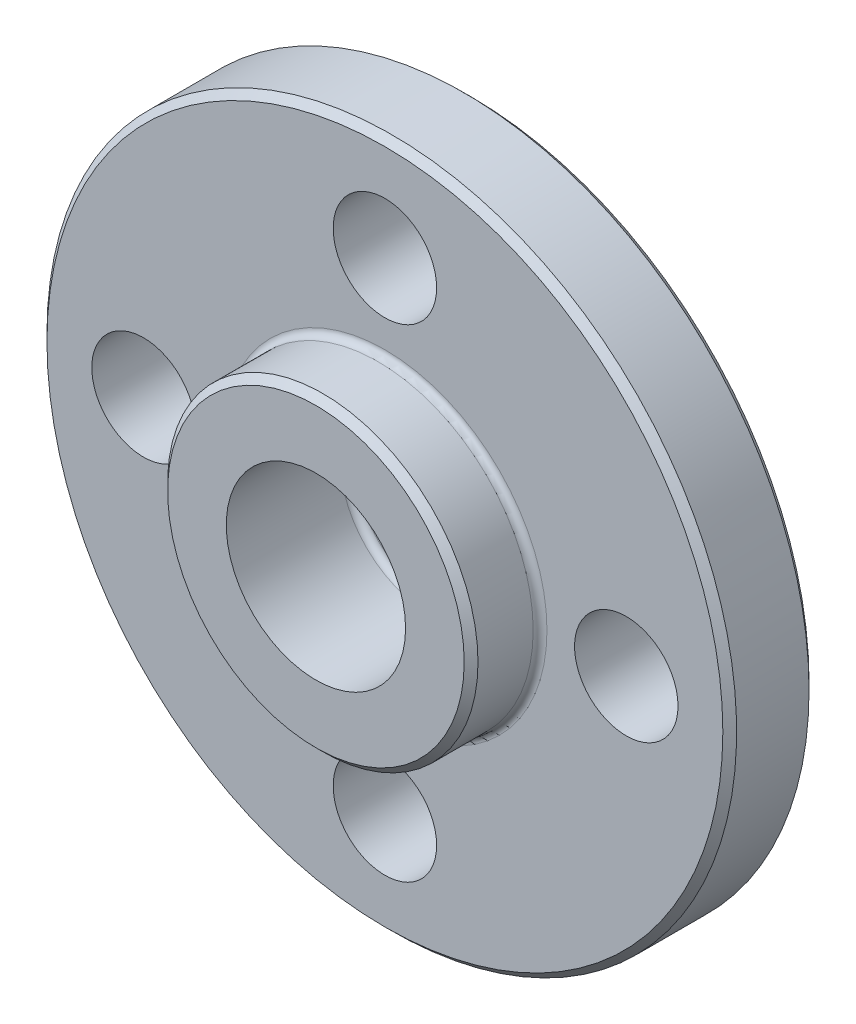
SolidWorks part; units mm, degrees
material "6061 Alloy"
ref_plane "Front Plane" through (0, 0, 0) normal (0, 0, 1) x (1, 0, 0)
ref_plane "Top Plane" through (0, 0, 0) normal (0, 1, 0) x (1, 0, 0)
ref_plane "Right Plane" through (0, 0, 0) normal (1, 0, 0) x (0, 0, -1)
sketch "Sketch1" plane through (0, 0, 0) normal (0, 0, 1) x (1, 0, 0)
  line L0 (0, 10) -> (0, -10) construction
  line L1 (-10, 0) -> (10, 0) construction
  circle A0 centre (0, 0) radius 10
  circle A1 centre (0, 0) radius 7 construction
  circle A2 centre (0, 7) radius 1.5
  circle A3 centre (7, 0) radius 1.5
  circle A4 centre (0, -7) radius 1.5
  circle A5 centre (-7, 0) radius 1.5
  circle A6 centre (0, 0) radius 1.5
  dimension "D1" = 20
  dimension "D2" = 14
  dimension "D3" = 3
extrude "Boss-Extrude1" add sketch "Sketch1" along normal blind 2.5
sketch "Sketch2" plane through (0, 0, 2.5) normal (0, 0, 1) x (1, 0, 0)
  circle A0 centre (0, 0) radius 4.5
  dimension "D1" = 9
extrude "Boss-Extrude2" add sketch "Sketch2" along normal blind 2
sketch "Sketch3" plane through (0, 0, 4.5) normal (0, 0, 1) x (1, 0, 0)
  circle A0 centre (0, 0) radius 2.6
  dimension "D1" = 5.2
extrude "Cut-Extrude1" cut sketch "Sketch3" against normal blind 3.5
chamfer "Chamfer1" distance 0.2 angle 45 3 edges at (10, 0, 0) (10, 0, 2.5) (4.5, 0, 4.5)
fillet "Fillet1" radius 0.2 2 edges at (2.6, 0, 1) (4.5, 0, 2.5)
